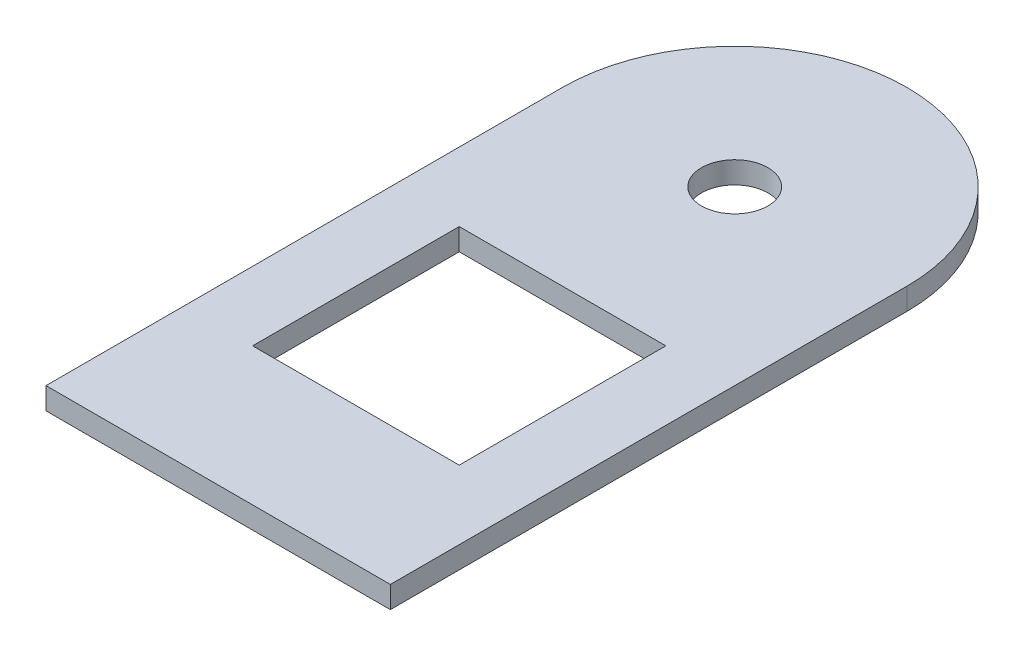
SolidWorks part; units mm, degrees
ref_plane "Front" through (0, 0, 0) normal (0, 0, 1) x (1, 0, 0)
ref_plane "Top" through (0, 0, 0) normal (0, 1, 0) x (1, 0, 0)
ref_plane "Right" through (0, 0, 0) normal (1, 0, 0) x (0, 0, -1)
sketch "Sketch1" plane through (0, 0, 0) normal (0, 1, 0) x (1, 0, 0)
  line L0 (25, 0) -> (25, -100) construction
  line L1 (0, 0) -> (50, 0)
  line L2 (0, 0) -> (0, -100)
  line L3 (0, -100) -> (50, -100)
  line L4 (50, 0) -> (50, -100)
  line L5 (0, -50) -> (50, -50) construction
  line L7 (10, -50) -> (40, -50)
  line L8 (10, -50) -> (10, -80)
  line L9 (10, -80) -> (40, -80)
  line L10 (40, -50) -> (40, -80)
  circle A0 centre (25, -25) radius 4.82
  circle A1 centre (25, -25) radius 25
  dimension "D3" = 9.64
  dimension "D4" = 25
  dimension "D1" = 100
  dimension "D2" = 50
  dimension "D5" = 30
  dimension "D6" = 30
extrude "Boss-Extrude1" add sketch "Sketch1" along normal blind 3.175 contours A1 L2 L3 L4 | A1 A0
